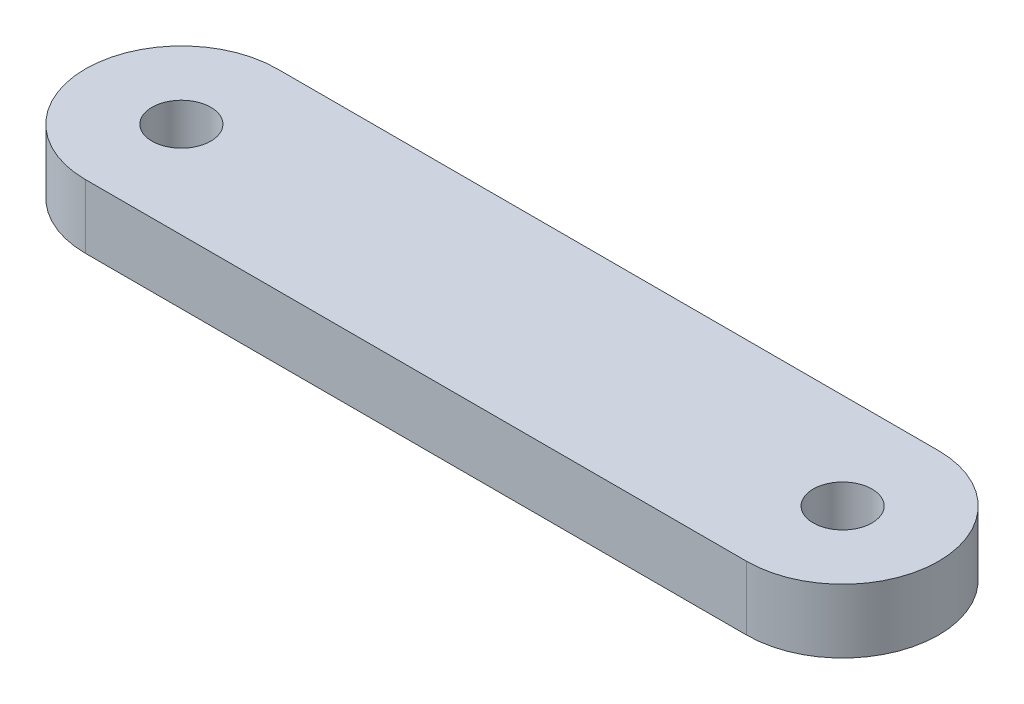
SolidWorks part; units mm, degrees
ref_plane "前视基准面" through (0, 0, 0) normal (0, 0, 1) x (1, 0, 0)
ref_plane "上视基准面" through (0, 0, 0) normal (0, 1, 0) x (1, 0, 0)
ref_plane "右视基准面" through (0, 0, 0) normal (1, 0, 0) x (0, 0, -1)
other "Configuration Table"
sketch "草图1" plane through (0, 0, 0) normal (0, 1, 0) x (1, 0, 0)
  line L1 (-25.8567, 7.5) -> (25.8567, 7.5)
  line L3 (-25.8567, -7.5) -> (25.8567, -7.5)
  line L5 (-25.8567, 7.5) -> (25.8567, -7.5) construction
  line L6 (-25.8567, -7.5) -> (25.8567, 7.5) construction
  arc A0 (-25.8567, 7.5) -> (-25.8567, -7.5) centre (-25.8567, 0) ccw
  arc A1 (25.8567, 7.5) -> (25.8567, -7.5) centre (25.8567, 0) cw
  circle A2 centre (-25.8567, 0) radius 2.3
  circle A3 centre (25.8567, 0) radius 2.3
  point P0 (0, 0)
  dimension "D3" = 4.6
  dimension "D4" = 4.6
  dimension "D1" = 51.7134
  dimension "D2" = 15
extrude "凸台-拉伸1" add sketch "草图1" along normal blind 5
equation "\"fi\"=4.6"
equation "\"b0\"= 75.6'ground"
equation "\"b1\"= \"b0\" *1.4/ 2'rocker"
equation "\"width\"=15"
equation "\"depth\"=5"
equation "\"b2\"= \"b0\"'coupler"
equation "\"b3\"= \"b0\" / 2'coupler"
equation "\"b4\"= \"b0\" *2'leg"
equation "\"angle\"= 40*pi/180'ground水平夹角"
equation "\"b5\"=(\"b2\"^2+\"b4\"^2)^0.5'斜边"
equation "\"D3@草图1\"=\"fi\""
equation "\"D4@草图1\"=\"fi\""
equation "\"D1@凸台-拉伸1\"=\"depth\""
equation "\"D2@草图1\"=\"width\""
equation "\"boff\" = \"b0\" * sin ( \"angle\" / 2 ) * 2"
equation "\"D1@草图1\"=\"boff\""
